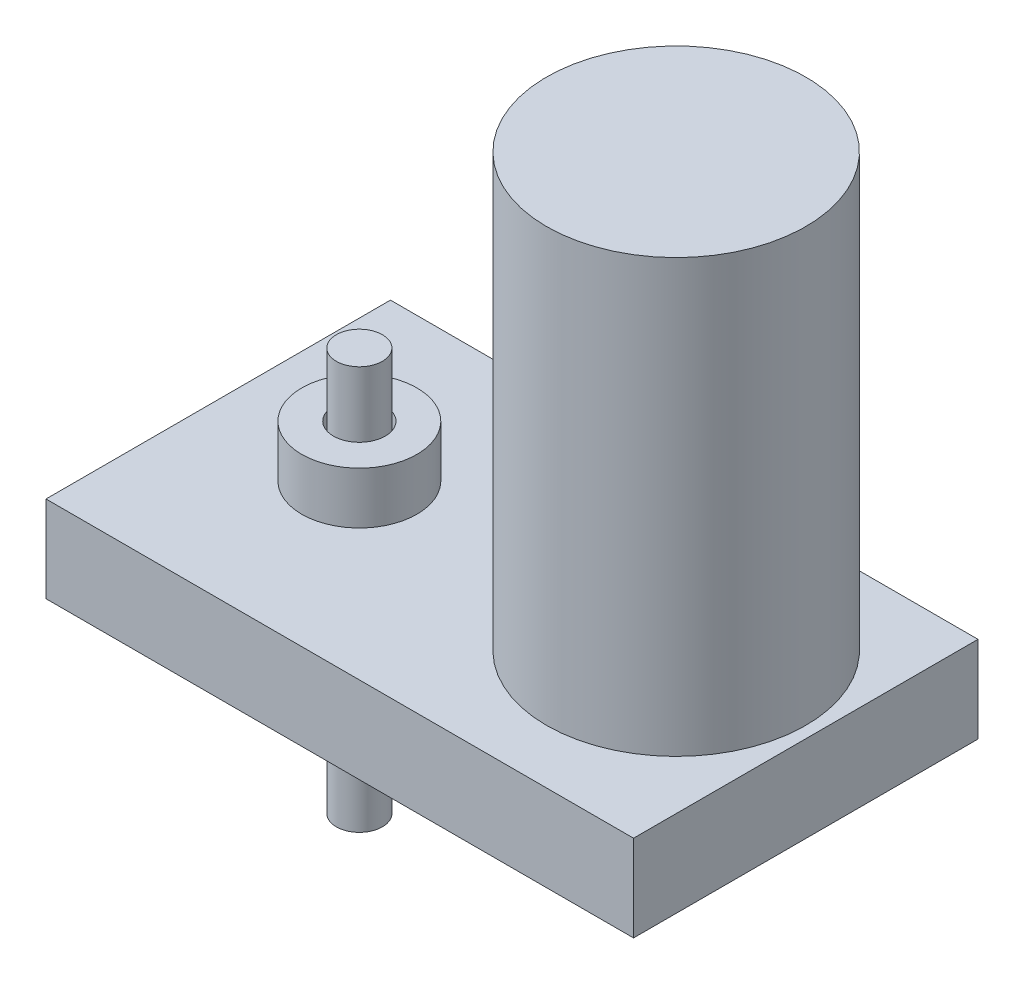
SolidWorks part; units mm, degrees
ref_plane "Front Plane" through (0, 0, 0) normal (0, 0, 1) x (1, 0, 0)
ref_plane "Top Plane" through (0, 0, 0) normal (0, 1, 0) x (1, 0, 0)
ref_plane "Right Plane" through (0, 0, 0) normal (1, 0, 0) x (0, 0, -1)
sketch "Sketch1" plane through (0, 0, 0) normal (0, 1, 0) x (1, 0, 0)
  line L0 (-51, 0) -> (-26.5, 0)
  line L1 (-51, 29.9) -> (51, 29.9)
  line L2 (-51, 29.9) -> (-51, -29.9)
  line L3 (-51, -29.9) -> (51, -29.9)
  line L4 (51, 29.9) -> (51, -29.9)
  line L5 (-51, 29.9) -> (51, -29.9) construction
  line L6 (-51, -29.9) -> (51, 29.9) construction
  circle A0 centre (-26.5, 0) radius 4
  point P0 (0, 0)
extrude "Boss-Extrude1" add sketch "Sketch1" along normal blind 15
sketch "Sketch3" plane through (0, 15, 0) normal (0, 1, 0) x (1, 0, 0)
  line L0 (51, 0) -> (28.5, 0)
  line L1 (51, 29.9) -> (51, -29.9) construction
  circle A0 centre (28.5, 0) radius 5
extrude "Boss-Extrude3" add sketch "Sketch3" along normal blind 2
sketch "Sketch4" plane through (0, 17, 0) normal (0, 1, 0) x (1, 0, 0)
  circle A0 centre (28.5, 0) radius 22.5
extrude "Boss-Extrude4" add sketch "Sketch4" along normal blind 75
sketch "Sketch5" plane through (0, 15, 0) normal (0, 1, 0) x (1, 0, 0)
  circle A0 centre (-26.5, 0) radius 10
extrude "Boss-Extrude5" add sketch "Sketch5" along normal blind 9
sketch "Sketch6" plane through (0, 24, 0) normal (0, 1, 0) x (1, 0, 0)
  circle A0 centre (-26.5, 0) radius 4.5
extrude "Cut-Extrude1" cut sketch "Sketch6" against normal blind 9
sketch "Sketch7" plane through (0, 15, 0) normal (0, 1, 0) x (1, 0, 0)
  circle A0 centre (-26.5, 0) radius 4
extrude "Boss-Extrude6" add sketch "Sketch7" along normal blind 20 separate body
sketch "Sketch8" plane through (0, 0, 0) normal (0, -1, 0) x (1, 0, 0)
  circle A0 centre (-26.5, 0) radius 10
  circle A1 centre (-26.5, 0) radius 4.5
extrude "Boss-Extrude7" add sketch "Sketch8" along normal blind 10
sketch "Sketch9" plane through (0, 0, 0) normal (0, -1, 0) x (1, 0, 0)
  circle A0 centre (-26.5, 0) radius 4
extrude "Boss-Extrude8" add sketch "Sketch9" along normal blind 35 separate body
